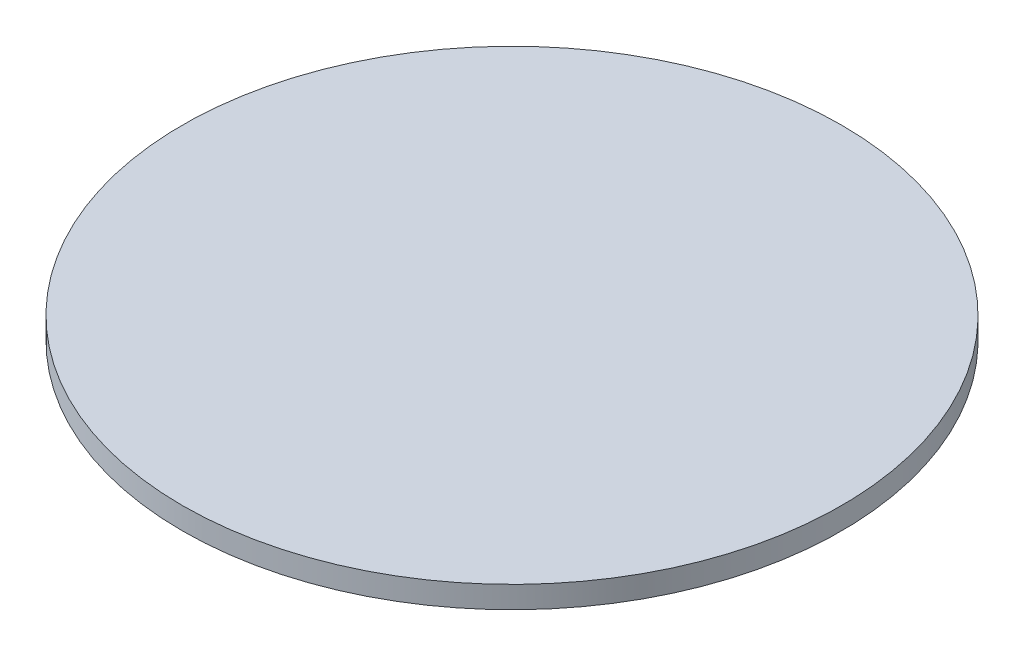
SolidWorks part; units mm, degrees
ref_plane "Front Plane" through (0, 0, 0) normal (0, 0, 1) x (1, 0, 0)
ref_plane "Top Plane" through (0, 0, 0) normal (0, 1, 0) x (1, 0, 0)
ref_plane "Right Plane" through (0, 0, 0) normal (1, 0, 0) x (0, 0, -1)
sketch "Sketch1" plane through (0, 0, 0) normal (0, 1, 0) x (1, 0, 0)
  circle A0 centre (0, 0) radius 150
  dimension "D1" = 300
extrude "Boss-Extrude1" add sketch "Sketch1" along normal blind 10
